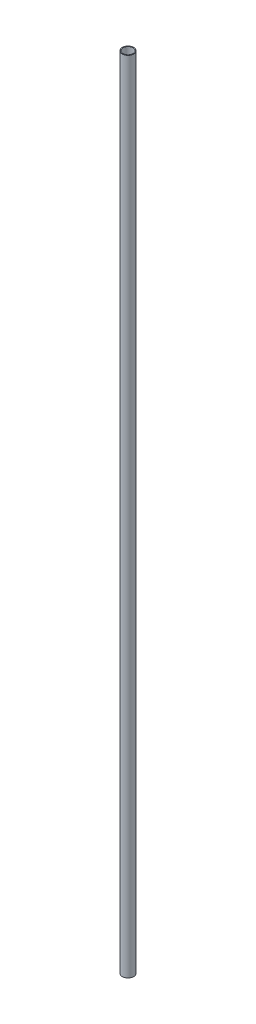
SolidWorks part; units mm, degrees
material "6061-T6 (SS)"
ref_plane "Front Plane" through (0, 0, 0) normal (0, 0, 1) x (1, 0, 0)
ref_plane "Top Plane" through (0, 0, 0) normal (0, 1, 0) x (1, 0, 0)
ref_plane "Right Plane" through (0, 0, 0) normal (1, 0, 0) x (0, 0, -1)
sketch "Sketch1" plane through (0, 0, 0) normal (0, 1, 0) x (1, 0, 0)
  circle A0 centre (0, 0) radius 9.525
  circle A1 centre (0, 0) radius 8.2804
  dimension "D1" = 19.05
  dimension "D2" = 16.5608
extrude "Boss-Extrude1" add sketch "Sketch1" along normal blind 1320.8
ref_point "Point2"
